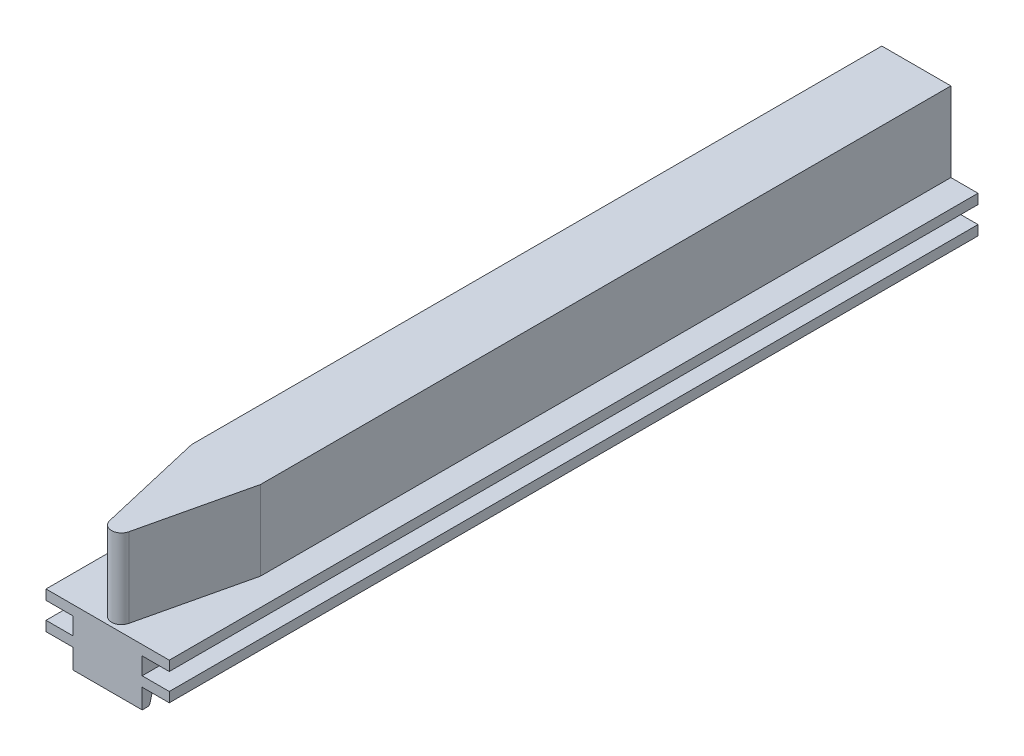
SolidWorks part; units mm, degrees
ref_plane "Ön Düzlem" through (0, 0, 0) normal (0, 0, 1) x (1, 0, 0)
ref_plane "Üst Düzlem" through (0, 0, 0) normal (0, 1, 0) x (1, 0, 0)
ref_plane "Sağ Düzlem" through (0, 0, 0) normal (1, 0, 0) x (0, 0, -1)
sketch "Çizim2" plane through (0, 0, 0) normal (0, 0, 1) x (1, 0, 0)
  line L0 (19.5, 0) -> (25, 0)
  line L1 (0, 0) -> (5.5, 0)
  line L2 (0, 0) -> (0, 2.8)
  line L3 (0, 2.8) -> (25, 2.8)
  line L4 (25, 0) -> (25, 2.8)
  line L6 (5.5, 0) -> (5.5, -2.8)
  line L7 (5.5, -2.8) -> (19.5, -2.8)
  line L8 (19.5, 0) -> (19.5, -2.8)
  dimension "D1" = 2.8
  dimension "D2" = 2.8
  dimension "D3" = 25
  dimension "D4" = 14
  dimension "D5" = 5.5
extrude "Yükseklik-Ekstrüzyon1" add sketch "Çizim2" along normal blind 170
sketch "Çizim3" plane through (19.5, 0, 0) normal (1, 0, 0) x (0, 0, -1)
  line L0 (0, 0) -> (0, 2.8) construction
  line L1 (-170, -2.8) -> (0, -2.8)
  line L2 (-170, -2.8) -> (-170, -22.8)
  line L3 (-167, -22.8) -> (-165, -22.8)
  line L4 (0, -2.8) -> (0, -22.8)
  line L5 (-170, -22.8) -> (-169.5947, -24.4213)
  line L6 (-169.1096, -24.8) -> (-167.8904, -24.8)
  line L7 (-167.4053, -24.4213) -> (-167, -22.8)
  line L8 (-162.4053, -24.4213) -> (-162, -22.8)
  line L9 (-164.1096, -24.8) -> (-162.8904, -24.8)
  line L10 (-165, -22.8) -> (-164.5947, -24.4213)
  line L11 (-157.4053, -24.4213) -> (-157, -22.8)
  line L12 (-159.1096, -24.8) -> (-157.8904, -24.8)
  line L13 (-160, -22.8) -> (-159.5947, -24.4213)
  line L14 (-152.4053, -24.4213) -> (-152, -22.8)
  line L15 (-154.1096, -24.8) -> (-152.8904, -24.8)
  line L16 (-155, -22.8) -> (-154.5947, -24.4213)
  line L17 (-147.4053, -24.4213) -> (-147, -22.8)
  line L18 (-149.1096, -24.8) -> (-147.8904, -24.8)
  line L19 (-150, -22.8) -> (-149.5947, -24.4213)
  line L20 (-142.4053, -24.4213) -> (-142, -22.8)
  line L21 (-144.1096, -24.8) -> (-142.8904, -24.8)
  line L22 (-145, -22.8) -> (-144.5947, -24.4213)
  line L23 (-137.4053, -24.4213) -> (-137, -22.8)
  line L24 (-139.1096, -24.8) -> (-137.8904, -24.8)
  line L25 (-140, -22.8) -> (-139.5947, -24.4213)
  line L26 (-132.4053, -24.4213) -> (-132, -22.8)
  line L27 (-134.1096, -24.8) -> (-132.8904, -24.8)
  line L28 (-135, -22.8) -> (-134.5947, -24.4213)
  line L29 (-127.4053, -24.4213) -> (-127, -22.8)
  line L30 (-129.1096, -24.8) -> (-127.8904, -24.8)
  line L31 (-130, -22.8) -> (-129.5947, -24.4213)
  line L32 (-122.4053, -24.4213) -> (-122, -22.8)
  line L33 (-124.1096, -24.8) -> (-122.8904, -24.8)
  line L34 (-125, -22.8) -> (-124.5947, -24.4213)
  line L35 (-117.4053, -24.4213) -> (-117, -22.8)
  line L36 (-119.1096, -24.8) -> (-117.8904, -24.8)
  line L37 (-120, -22.8) -> (-119.5947, -24.4213)
  line L38 (-112.4053, -24.4213) -> (-112, -22.8)
  line L39 (-114.1096, -24.8) -> (-112.8904, -24.8)
  line L40 (-115, -22.8) -> (-114.5947, -24.4213)
  line L41 (-107.4053, -24.4213) -> (-107, -22.8)
  line L42 (-109.1096, -24.8) -> (-107.8904, -24.8)
  line L43 (-110, -22.8) -> (-109.5947, -24.4213)
  line L44 (-102.4053, -24.4213) -> (-102, -22.8)
  line L45 (-104.1096, -24.8) -> (-102.8904, -24.8)
  line L46 (-105, -22.8) -> (-104.5947, -24.4213)
  line L47 (-97.4053, -24.4213) -> (-97, -22.8)
  line L48 (-99.1096, -24.8) -> (-97.8904, -24.8)
  line L49 (-100, -22.8) -> (-99.5947, -24.4213)
  line L50 (-92.4053, -24.4213) -> (-92, -22.8)
  line L51 (-94.1096, -24.8) -> (-92.8904, -24.8)
  line L52 (-95, -22.8) -> (-94.5947, -24.4213)
  line L53 (-87.4053, -24.4213) -> (-87, -22.8)
  line L54 (-89.1096, -24.8) -> (-87.8904, -24.8)
  line L55 (-90, -22.8) -> (-89.5947, -24.4213)
  line L56 (-82.4053, -24.4213) -> (-82, -22.8)
  line L57 (-84.1096, -24.8) -> (-82.8904, -24.8)
  line L58 (-85, -22.8) -> (-84.5947, -24.4213)
  line L59 (-77.4053, -24.4213) -> (-77, -22.8)
  line L60 (-79.1096, -24.8) -> (-77.8904, -24.8)
  line L61 (-80, -22.8) -> (-79.5947, -24.4213)
  line L62 (-72.4053, -24.4213) -> (-72, -22.8)
  line L63 (-74.1096, -24.8) -> (-72.8904, -24.8)
  line L64 (-75, -22.8) -> (-74.5947, -24.4213)
  line L65 (-67.4053, -24.4213) -> (-67, -22.8)
  line L66 (-69.1096, -24.8) -> (-67.8904, -24.8)
  line L67 (-70, -22.8) -> (-69.5947, -24.4213)
  line L68 (-62.4053, -24.4213) -> (-62, -22.8)
  line L69 (-64.1096, -24.8) -> (-62.8904, -24.8)
  line L70 (-65, -22.8) -> (-64.5947, -24.4213)
  line L71 (-57.4053, -24.4213) -> (-57, -22.8)
  line L72 (-59.1096, -24.8) -> (-57.8904, -24.8)
  line L73 (-60, -22.8) -> (-59.5947, -24.4213)
  line L74 (-52.4053, -24.4213) -> (-52, -22.8)
  line L75 (-54.1096, -24.8) -> (-52.8904, -24.8)
  line L76 (-55, -22.8) -> (-54.5947, -24.4213)
  line L77 (-47.4053, -24.4213) -> (-47, -22.8)
  line L78 (-49.1096, -24.8) -> (-47.8904, -24.8)
  line L79 (-50, -22.8) -> (-49.5947, -24.4213)
  line L80 (-42.4053, -24.4213) -> (-42, -22.8)
  line L81 (-44.1096, -24.8) -> (-42.8904, -24.8)
  line L82 (-45, -22.8) -> (-44.5947, -24.4213)
  line L83 (-162, -22.8) -> (-160, -22.8)
  line L84 (-157, -22.8) -> (-155, -22.8)
  line L85 (-152, -22.8) -> (-150, -22.8)
  line L86 (-147, -22.8) -> (-145, -22.8)
  line L87 (-142, -22.8) -> (-140, -22.8)
  line L88 (-137, -22.8) -> (-135, -22.8)
  line L89 (-132, -22.8) -> (-130, -22.8)
  line L90 (-127, -22.8) -> (-125, -22.8)
  line L91 (-122, -22.8) -> (-120, -22.8)
  line L92 (-117, -22.8) -> (-115, -22.8)
  line L93 (-112, -22.8) -> (-110, -22.8)
  line L94 (-107, -22.8) -> (-105, -22.8)
  line L95 (-102, -22.8) -> (-100, -22.8)
  line L96 (-97, -22.8) -> (-95, -22.8)
  line L97 (-92, -22.8) -> (-90, -22.8)
  line L98 (-87, -22.8) -> (-85, -22.8)
  line L99 (-82, -22.8) -> (-80, -22.8)
  line L100 (-77, -22.8) -> (-75, -22.8)
  line L101 (-42, -22.8) -> (-40, -22.8)
  line L102 (-47, -22.8) -> (-45, -22.8)
  line L103 (-52, -22.8) -> (-50, -22.8)
  line L104 (-57, -22.8) -> (-55, -22.8)
  line L105 (-62, -22.8) -> (-60, -22.8)
  line L106 (-67, -22.8) -> (-65, -22.8)
  line L107 (-72, -22.8) -> (-70, -22.8)
  line L108 (-37.4053, -24.4213) -> (-37, -22.8)
  line L109 (-39.1096, -24.8) -> (-37.8904, -24.8)
  line L110 (-40, -22.8) -> (-39.5947, -24.4213)
  line L111 (-32.4053, -24.4213) -> (-32, -22.8)
  line L112 (-34.1096, -24.8) -> (-32.8904, -24.8)
  line L113 (-35, -22.8) -> (-34.5947, -24.4213)
  line L114 (-27.4053, -24.4213) -> (-27, -22.8)
  line L115 (-29.1096, -24.8) -> (-27.8904, -24.8)
  line L116 (-30, -22.8) -> (-29.5947, -24.4213)
  line L117 (-22.4053, -24.4213) -> (-22, -22.8)
  line L118 (-24.1096, -24.8) -> (-22.8904, -24.8)
  line L119 (-25, -22.8) -> (-24.5947, -24.4213)
  line L120 (-17.4053, -24.4213) -> (-17, -22.8)
  line L121 (-19.1096, -24.8) -> (-17.8904, -24.8)
  line L122 (-20, -22.8) -> (-19.5947, -24.4213)
  line L123 (-12.4053, -24.4213) -> (-12, -22.8)
  line L124 (-14.1096, -24.8) -> (-12.8904, -24.8)
  line L125 (-15, -22.8) -> (-14.5947, -24.4213)
  line L126 (-37, -22.8) -> (-35, -22.8)
  line L127 (-32, -22.8) -> (-30, -22.8)
  line L128 (-27, -22.8) -> (-25, -22.8)
  line L129 (-22, -22.8) -> (-20, -22.8)
  line L130 (-17, -22.8) -> (-15, -22.8)
  line L131 (-12, -22.8) -> (0, -22.8)
  arc A0 (-167.8904, -24.8) -> (-167.4053, -24.4213) centre (-167.8904, -24.3) ccw
  arc A1 (-169.5947, -24.4213) -> (-169.1096, -24.8) centre (-169.1096, -24.3) ccw
  arc A2 (-162.8904, -24.8) -> (-162.4053, -24.4213) centre (-162.8904, -24.3) ccw
  arc A3 (-164.5947, -24.4213) -> (-164.1096, -24.8) centre (-164.1096, -24.3) ccw
  arc A4 (-157.8904, -24.8) -> (-157.4053, -24.4213) centre (-157.8904, -24.3) ccw
  arc A5 (-159.5947, -24.4213) -> (-159.1096, -24.8) centre (-159.1096, -24.3) ccw
  arc A6 (-152.8904, -24.8) -> (-152.4053, -24.4213) centre (-152.8904, -24.3) ccw
  arc A7 (-154.5947, -24.4213) -> (-154.1096, -24.8) centre (-154.1096, -24.3) ccw
  arc A8 (-147.8904, -24.8) -> (-147.4053, -24.4213) centre (-147.8904, -24.3) ccw
  arc A9 (-149.5947, -24.4213) -> (-149.1096, -24.8) centre (-149.1096, -24.3) ccw
  arc A10 (-142.8904, -24.8) -> (-142.4053, -24.4213) centre (-142.8904, -24.3) ccw
  arc A11 (-144.5947, -24.4213) -> (-144.1096, -24.8) centre (-144.1096, -24.3) ccw
  arc A12 (-137.8904, -24.8) -> (-137.4053, -24.4213) centre (-137.8904, -24.3) ccw
  arc A13 (-139.5947, -24.4213) -> (-139.1096, -24.8) centre (-139.1096, -24.3) ccw
  arc A14 (-132.8904, -24.8) -> (-132.4053, -24.4213) centre (-132.8904, -24.3) ccw
  arc A15 (-134.5947, -24.4213) -> (-134.1096, -24.8) centre (-134.1096, -24.3) ccw
  arc A16 (-127.8904, -24.8) -> (-127.4053, -24.4213) centre (-127.8904, -24.3) ccw
  arc A17 (-129.5947, -24.4213) -> (-129.1096, -24.8) centre (-129.1096, -24.3) ccw
  arc A18 (-122.8904, -24.8) -> (-122.4053, -24.4213) centre (-122.8904, -24.3) ccw
  arc A19 (-124.5947, -24.4213) -> (-124.1096, -24.8) centre (-124.1096, -24.3) ccw
  arc A20 (-117.8904, -24.8) -> (-117.4053, -24.4213) centre (-117.8904, -24.3) ccw
  arc A21 (-119.5947, -24.4213) -> (-119.1096, -24.8) centre (-119.1096, -24.3) ccw
  arc A22 (-112.8904, -24.8) -> (-112.4053, -24.4213) centre (-112.8904, -24.3) ccw
  arc A23 (-114.5947, -24.4213) -> (-114.1096, -24.8) centre (-114.1096, -24.3) ccw
  arc A24 (-107.8904, -24.8) -> (-107.4053, -24.4213) centre (-107.8904, -24.3) ccw
  arc A25 (-109.5947, -24.4213) -> (-109.1096, -24.8) centre (-109.1096, -24.3) ccw
  arc A26 (-102.8904, -24.8) -> (-102.4053, -24.4213) centre (-102.8904, -24.3) ccw
  arc A27 (-104.5947, -24.4213) -> (-104.1096, -24.8) centre (-104.1096, -24.3) ccw
  arc A28 (-97.8904, -24.8) -> (-97.4053, -24.4213) centre (-97.8904, -24.3) ccw
  arc A29 (-99.5947, -24.4213) -> (-99.1096, -24.8) centre (-99.1096, -24.3) ccw
  arc A30 (-92.8904, -24.8) -> (-92.4053, -24.4213) centre (-92.8904, -24.3) ccw
  arc A31 (-94.5947, -24.4213) -> (-94.1096, -24.8) centre (-94.1096, -24.3) ccw
  arc A32 (-87.8904, -24.8) -> (-87.4053, -24.4213) centre (-87.8904, -24.3) ccw
  arc A33 (-89.5947, -24.4213) -> (-89.1096, -24.8) centre (-89.1096, -24.3) ccw
  arc A34 (-82.8904, -24.8) -> (-82.4053, -24.4213) centre (-82.8904, -24.3) ccw
  arc A35 (-84.5947, -24.4213) -> (-84.1096, -24.8) centre (-84.1096, -24.3) ccw
  arc A36 (-77.8904, -24.8) -> (-77.4053, -24.4213) centre (-77.8904, -24.3) ccw
  arc A37 (-79.5947, -24.4213) -> (-79.1096, -24.8) centre (-79.1096, -24.3) ccw
  arc A38 (-72.8904, -24.8) -> (-72.4053, -24.4213) centre (-72.8904, -24.3) ccw
  arc A39 (-74.5947, -24.4213) -> (-74.1096, -24.8) centre (-74.1096, -24.3) ccw
  arc A40 (-67.8904, -24.8) -> (-67.4053, -24.4213) centre (-67.8904, -24.3) ccw
  arc A41 (-69.5947, -24.4213) -> (-69.1096, -24.8) centre (-69.1096, -24.3) ccw
  arc A42 (-62.8904, -24.8) -> (-62.4053, -24.4213) centre (-62.8904, -24.3) ccw
  arc A43 (-64.5947, -24.4213) -> (-64.1096, -24.8) centre (-64.1096, -24.3) ccw
  arc A44 (-57.8904, -24.8) -> (-57.4053, -24.4213) centre (-57.8904, -24.3) ccw
  arc A45 (-59.5947, -24.4213) -> (-59.1096, -24.8) centre (-59.1096, -24.3) ccw
  arc A46 (-52.8904, -24.8) -> (-52.4053, -24.4213) centre (-52.8904, -24.3) ccw
  arc A47 (-54.5947, -24.4213) -> (-54.1096, -24.8) centre (-54.1096, -24.3) ccw
  arc A48 (-47.8904, -24.8) -> (-47.4053, -24.4213) centre (-47.8904, -24.3) ccw
  arc A49 (-49.5947, -24.4213) -> (-49.1096, -24.8) centre (-49.1096, -24.3) ccw
  arc A50 (-42.8904, -24.8) -> (-42.4053, -24.4213) centre (-42.8904, -24.3) ccw
  arc A51 (-44.5947, -24.4213) -> (-44.1096, -24.8) centre (-44.1096, -24.3) ccw
  arc A52 (-37.8904, -24.8) -> (-37.4053, -24.4213) centre (-37.8904, -24.3) ccw
  arc A53 (-39.5947, -24.4213) -> (-39.1096, -24.8) centre (-39.1096, -24.3) ccw
  arc A54 (-32.8904, -24.8) -> (-32.4053, -24.4213) centre (-32.8904, -24.3) ccw
  arc A55 (-34.5947, -24.4213) -> (-34.1096, -24.8) centre (-34.1096, -24.3) ccw
  arc A56 (-27.8904, -24.8) -> (-27.4053, -24.4213) centre (-27.8904, -24.3) ccw
  arc A57 (-29.5947, -24.4213) -> (-29.1096, -24.8) centre (-29.1096, -24.3) ccw
  arc A58 (-22.8904, -24.8) -> (-22.4053, -24.4213) centre (-22.8904, -24.3) ccw
  arc A59 (-24.5947, -24.4213) -> (-24.1096, -24.8) centre (-24.1096, -24.3) ccw
  arc A60 (-17.8904, -24.8) -> (-17.4053, -24.4213) centre (-17.8904, -24.3) ccw
  arc A61 (-19.5947, -24.4213) -> (-19.1096, -24.8) centre (-19.1096, -24.3) ccw
  arc A62 (-12.8904, -24.8) -> (-12.4053, -24.4213) centre (-12.8904, -24.3) ccw
  arc A63 (-14.5947, -24.4213) -> (-14.1096, -24.8) centre (-14.1096, -24.3) ccw
  point P12 (-167.5, -24.8)
  point P15 (-169.5, -24.8)
  dimension "D5" = 0.5
  dimension "D1" = 20
  dimension "D2" = 2
  dimension "D3" = 3
  dimension "D4" = 2
  dimension "D7" = 2
  dimension "D6" = 32
extrude "Yükseklik-Ekstrüzyon2" add sketch "Çizim3" against normal blind 14
sketch "Çizim4" plane through (0, 0, 0) normal (0, 0, -1) x (-1, 0, 0)
  line L0 (-25, 2.8) -> (0, 2.8) construction
  line L1 (-25, -15.3) -> (0, -15.3)
  line L2 (-25, -15.3) -> (-25, -13.3)
  line L3 (-25, -13.3) -> (0, -13.3)
  line L4 (0, -15.3) -> (0, -13.3)
  line L5 (-25, 0) -> (-25, 2.8) construction
  line L6 (-5.5, -22.8) -> (-19.5, -22.8) construction
  line L7 (-25, -18.8) -> (0, -18.8)
  line L8 (-25, -18.8) -> (-25, -20.8)
  line L9 (-25, -20.8) -> (0, -20.8)
  line L10 (0, -18.8) -> (0, -20.8)
  dimension "D1" = 2
  dimension "D2" = 3.5
  dimension "D3" = 2
extrude "Yükseklik-Ekstrüzyon3" add sketch "Çizim4" against normal up to surface (170 mm away) up to face at (12.5, -5, 170)
pattern_linear "LÇoğaltma1" count 2 spacing 10 along (0, 0, -1) of "Yükseklik-Ekstrüzyon2"
sketch "Çizim6" plane through (5.5, 0, 0) normal (-1, 0, 0) x (0, 0, 1)
  line L0 (2, -22.8) -> (-10, -22.8) construction
  line L1 (-10, -2.8) -> (0, -2.8)
  line L2 (-10, -2.8) -> (-10, -22.8)
  line L3 (-10, -22.8) -> (0, -22.8)
  line L4 (0, -2.8) -> (0, -22.8)
extrude "Kes-Ekstrüzyon1" cut sketch "Çizim6" against normal blind 30
sketch "Çizim7" plane through (0, 0, 0) normal (0, 0, -1) x (-1, 0, 0)
  line L1 (-19.5, 0) -> (-25, 0)
  line L2 (-19.5, 0) -> (-19.5, 2.8)
  line L3 (-19.5, 2.8) -> (-25, 2.8)
  line L4 (-25, 0) -> (-25, 2.8)
  line L5 (-5.5, 0) -> (0, 0)
  line L6 (-5.5, 0) -> (-5.5, 2.8)
  line L7 (-5.5, 2.8) -> (0, 2.8)
  line L8 (0, 0) -> (0, 2.8)
extrude "Kes-Ekstrüzyon2" cut sketch "Çizim7" against normal blind 179
sketch "Çizim8" plane through (0, 2.8, 0) normal (0, 1, 0) x (1, 0, 0)
  line L0 (5.5, -140) -> (12.5, -170)
  line L1 (5.5, 0) -> (5.5, -170) construction
  line L2 (19.5, -170) -> (5.5, -170) construction
  line L3 (12.5, -170) -> (19.5, -140)
  line L4 (19.5, -170) -> (19.5, 0) construction
  line L5 (5.5, -140) -> (5.5, -170)
  line L6 (5.5, -170) -> (19.5, -170)
  line L7 (19.5, -170) -> (19.5, 0) construction
  line L8 (19.5, -170) -> (19.5, -140)
  line M2 (5.5, 0) -> (5.5, -170)
  line M3 (5.5, -170) -> (19.5, -170)
  line M4 (19.5, -170) -> (19.5, 0)
  dimension "D1" = 30
extrude "Kes-Ekstrüzyon3" cut sketch "Çizim8" against normal blind 16.1 contours L0 M2 M3 | L3 M3 M4
fillet "Radyus1" radius 2 1 edges at (12.5, -5.25, 170)
sketch "Çizim10" plane through (0, 0, 170) normal (0, 0, 1) x (1, 0, 0)
  line L1 (-0.3604, -26.8746) -> (29.6963, -26.8746)
  line L2 (-0.3604, -26.8746) -> (-0.3604, 6.899)
  line L3 (-0.3604, 6.899) -> (29.6963, 6.899)
  line L4 (29.6963, -26.8746) -> (29.6963, 6.899)
extrude "Kes-Ekstrüzyon4" cut sketch "Çizim10" against normal blind 6
